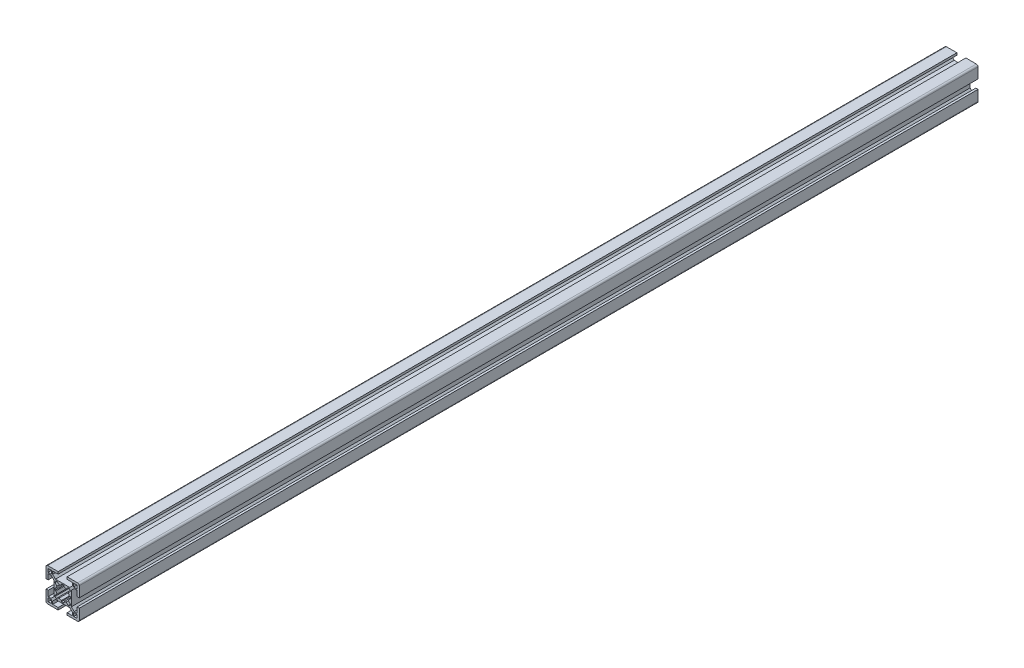
SolidWorks part; units mm, degrees
material "6063-T5"
ref_plane "Plano frontal" through (0, 0, 0) normal (0, 0, 1) x (1, 0, 0)
ref_plane "Plano superior" through (0, 0, 0) normal (0, 1, 0) x (1, 0, 0)
ref_plane "Plano direito" through (0, 0, 0) normal (1, 0, 0) x (0, 0, -1)
sketch "Esboço1" plane through (0, 0, 0) normal (0, 0, 1) x (1, 0, 0)
  line L0 (15, 13.5) -> (15, 4.05)
  line L1 (-13.5, 15) -> (-4.05, 15)
  line L8 (-9, 13) -> (-9, 10.4142)
  line L9 (-10, 13) -> (-10, 10)
  line L10 (-9, 13) -> (-4.05, 13)
  line L11 (-6.9, 1) -> (-6.9, 0)
  line L12 (-13, 13) -> (-10, 13)
  line L13 (-10.4142, 9) -> (-7.9, 6.4858)
  line L14 (-6.9, 1) -> (-5.9668, 1)
  line L15 (-15, 4.05) -> (-13, 4.05)
  line L16 (-6.4858, 7.9) -> (0, 7.9)
  line L17 (-4.9126, 6.9) -> (-3.1673, 5.1547)
  line L18 (-5.8279, 6.9) -> (-4.9126, 6.9)
  line L19 (-6.9, 5.8279) -> (-6.9, 4.9126)
  line L20 (-4.05, 15) -> (-4.05, 13)
  line L21 (13, 9) -> (10.4142, 9)
  line L22 (-1, 6.9) -> (-1, 5.9668)
  line L23 (-6.9, 4.9126) -> (-5.1547, 3.1673)
  line L24 (-5.8279, 6.9) -> (-6.9, 5.8279)
  line L25 (-7.9, 6.4858) -> (-7.9, 0)
  line L26 (13, 10) -> (10, 10)
  line L27 (-9, 10.4142) -> (-6.4858, 7.9)
  line L28 (13, 9) -> (13, 4.05)
  line L29 (-1, 6.9) -> (0, 6.9)
  line L30 (-6.4858, 6.9) -> (0, 6.9) construction
  line L31 (-13, 13) -> (-13, 10)
  line L32 (-13, 9) -> (-13, 4.05)
  line L33 (-15, 15) -> (-15, -15) construction
  line L34 (-15, 15) -> (15, 15) construction
  line L35 (-13, 10) -> (-10, 10)
  line L36 (-13, 9) -> (-10.4142, 9)
  line L37 (-13, 13) -> (13, 13) construction
  line L38 (-15, 13.5) -> (-15, 4.05)
  line L39 (1, 6.9) -> (0, 6.9)
  line L40 (13, 13) -> (13, 10)
  line L41 (-13, 13) -> (-13, -13) construction
  line L42 (9, 10.4142) -> (6.4858, 7.9)
  line L43 (1, 6.9) -> (1, 5.9668)
  line L44 (4.05, 15) -> (4.05, 13)
  line L45 (7.9, 6.4858) -> (7.9, 0)
  line L46 (6.9, 4.9126) -> (5.1547, 3.1673)
  line L47 (6.9, 5.8279) -> (6.9, 4.9126)
  line L48 (5.8279, 6.9) -> (4.9126, 6.9)
  line L49 (-7.9, 7.9) -> (7.9, 7.9) construction
  line L50 (15, 4.05) -> (13, 4.05)
  line L51 (6.9, 1) -> (5.9668, 1)
  line L52 (4.9126, 6.9) -> (3.1673, 5.1547)
  line L53 (6.9, 5.8279) -> (5.8279, 6.9)
  line L54 (6.4858, 7.9) -> (0, 7.9)
  line L55 (10.4142, 9) -> (7.9, 6.4858)
  line L56 (6.9, 1) -> (6.9, 0)
  line L57 (13, 13) -> (10, 13)
  line L58 (9, 13) -> (4.05, 13)
  line L59 (10, 13) -> (10, 10)
  line L60 (9, 13) -> (9, 10.4142)
  line L61 (13.5, 15) -> (4.05, 15)
  line L62 (13.5, -15) -> (4.05, -15)
  line L63 (9, -13) -> (9, -10.4142)
  line L64 (10, -13) -> (10, -10)
  line L65 (9, -13) -> (4.05, -13)
  line L66 (-7.9, 7.9) -> (-7.9, -7.9) construction
  line L67 (6.9, -1) -> (6.9, 0)
  line L68 (-15, -15) -> (15, -15) construction
  line L69 (15, 15) -> (15, -15) construction
  line L70 (13, 13) -> (13, -13) construction
  line L71 (-13, -13) -> (13, -13) construction
  line L72 (7.9, 7.9) -> (7.9, -7.9) construction
  line L73 (-7.9, -7.9) -> (7.9, -7.9) construction
  line L74 (13, -13) -> (10, -13)
  line L75 (10.4142, -9) -> (7.9, -6.4858)
  line L76 (6.9, -1) -> (5.9668, -1)
  line L77 (15, -4.05) -> (13, -4.05)
  line L78 (6.4858, -7.9) -> (0, -7.9)
  line L79 (4.9126, -6.9) -> (3.1673, -5.1547)
  line L80 (5.8279, -6.9) -> (4.9126, -6.9)
  line L81 (6.9, -5.8279) -> (6.9, -4.9126)
  line L82 (4.05, -15) -> (4.05, -13)
  line L83 (1, -6.9) -> (1, -5.9668)
  line L84 (6.9, -4.9126) -> (5.1547, -3.1673)
  line L85 (5.8279, -6.9) -> (6.9, -5.8279)
  line L86 (7.9, -6.4858) -> (7.9, 0)
  line L87 (9, -10.4142) -> (6.4858, -7.9)
  line L88 (1, -6.9) -> (0, -6.9)
  line L89 (13, -13) -> (13, -10)
  line L90 (13, -9) -> (13, -4.05)
  line L91 (13, -10) -> (10, -10)
  line L92 (13, -9) -> (10.4142, -9)
  line L93 (15, -13.5) -> (15, -4.05)
  line L94 (-15, -13.5) -> (-15, -4.05)
  line L95 (-13, -9) -> (-10.4142, -9)
  line L96 (-13, -10) -> (-10, -10)
  line L97 (-13, -9) -> (-13, -4.05)
  line L98 (-1, -6.9) -> (0, -6.9)
  line L99 (-13, -13) -> (-13, -10)
  line L100 (-9, -10.4142) -> (-6.4858, -7.9)
  line L101 (-1, -6.9) -> (-1, -5.9668)
  line L102 (-4.05, -15) -> (-4.05, -13)
  line L103 (-7.9, -6.4858) -> (-7.9, 0)
  line L104 (-6.9, -4.9126) -> (-5.1547, -3.1673)
  line L105 (-6.9, -5.8279) -> (-6.9, -4.9126)
  line L106 (-5.8279, -6.9) -> (-4.9126, -6.9)
  line L107 (-15, -4.05) -> (-13, -4.05)
  line L108 (-6.9, -1) -> (-5.9668, -1)
  line L109 (-4.9126, -6.9) -> (-3.1673, -5.1547)
  line L110 (-6.9, -5.8279) -> (-5.8279, -6.9)
  line L111 (-6.4858, -7.9) -> (0, -7.9)
  line L112 (-10.4142, -9) -> (-7.9, -6.4858)
  line L113 (-6.9, -1) -> (-6.9, 0)
  line L114 (-13, -13) -> (-10, -13)
  line L115 (-9, -13) -> (-4.05, -13)
  line L116 (-10, -13) -> (-10, -10)
  line L117 (-9, -13) -> (-9, -10.4142)
  line L118 (-13.5, -15) -> (-4.05, -15)
  arc A0 (-1, 5.9668) -> (-3.1673, 5.1547) centre (0, 0) ccw
  arc A1 (-5.9668, 1) -> (-5.1547, 3.1673) centre (0, 0) cw
  arc A2 (-13.5, 15) -> (-15, 13.5) centre (-13.5, 13.5) ccw
  arc A3 (5.9668, 1) -> (5.1547, 3.1673) centre (0, 0) ccw
  arc A4 (1, 5.9668) -> (3.1673, 5.1547) centre (0, 0) cw
  arc A5 (15, 13.5) -> (13.5, 15) centre (13.5, 13.5) ccw
  arc A6 (1, -5.9668) -> (3.1673, -5.1547) centre (0, 0) ccw
  arc A7 (5.9668, -1) -> (5.1547, -3.1673) centre (0, 0) cw
  arc A8 (13.5, -15) -> (15, -13.5) centre (13.5, -13.5) ccw
  arc A9 (-5.9668, -1) -> (-5.1547, -3.1673) centre (0, 0) ccw
  arc A10 (-1, -5.9668) -> (-3.1673, -5.1547) centre (0, 0) cw
  arc A11 (-15, -13.5) -> (-13.5, -15) centre (-13.5, -13.5) ccw
  point P139 (0, 0)
  dimension "D1" = 4
extrude "Ressalto-extrusão1" add sketch "Esboço1" along normal mid plane 810
